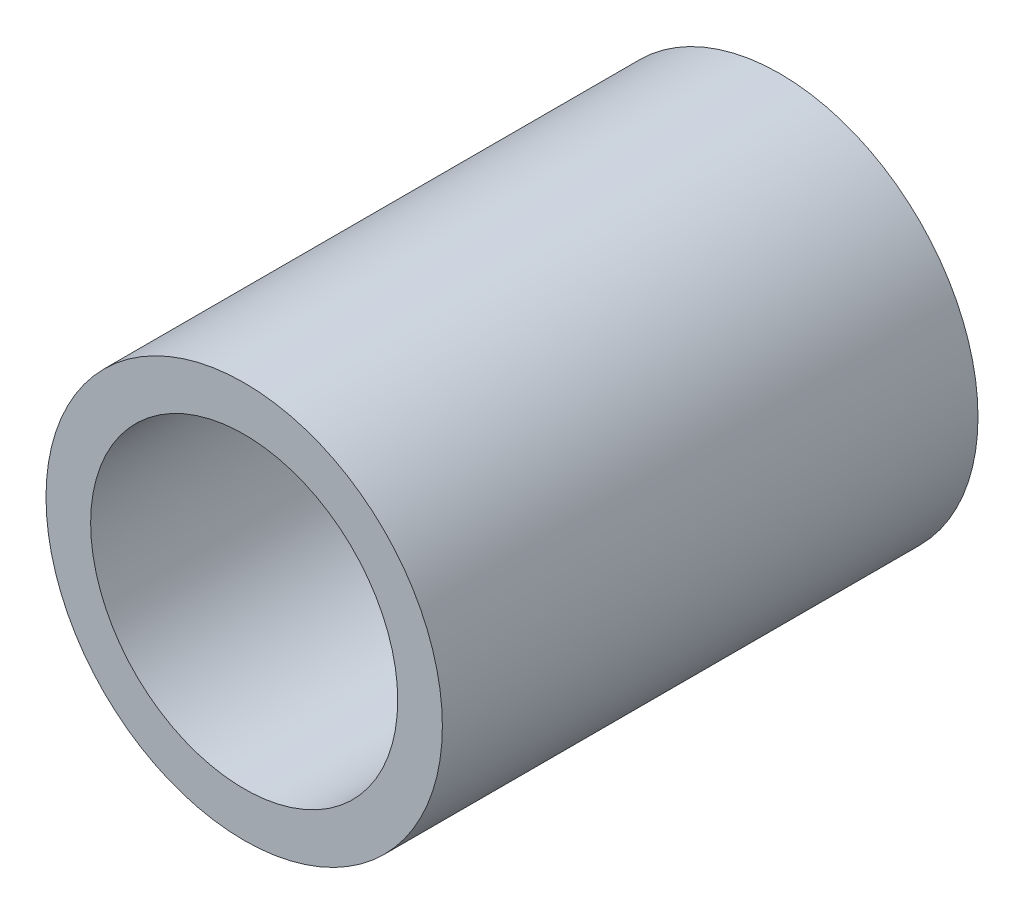
SolidWorks part; units mm, degrees
ref_plane "Front Plane" through (0, 0, 0) normal (0, 0, 1) x (1, 0, 0)
ref_plane "Top Plane" through (0, 0, 0) normal (0, 1, 0) x (1, 0, 0)
ref_plane "Right Plane" through (0, 0, 0) normal (1, 0, 0) x (0, 0, -1)
sketch "Sketch1" plane through (0, 0, 0) normal (0, 0, 1) x (1, 0, 0)
  circle A0 centre (0, 0) radius 17.2
  circle A1 centre (0, 0) radius 22.2
  dimension "D1" = 34.4
  dimension "D2" = 5
extrude "Boss-Extrude1" add sketch "Sketch1" along normal blind 60
